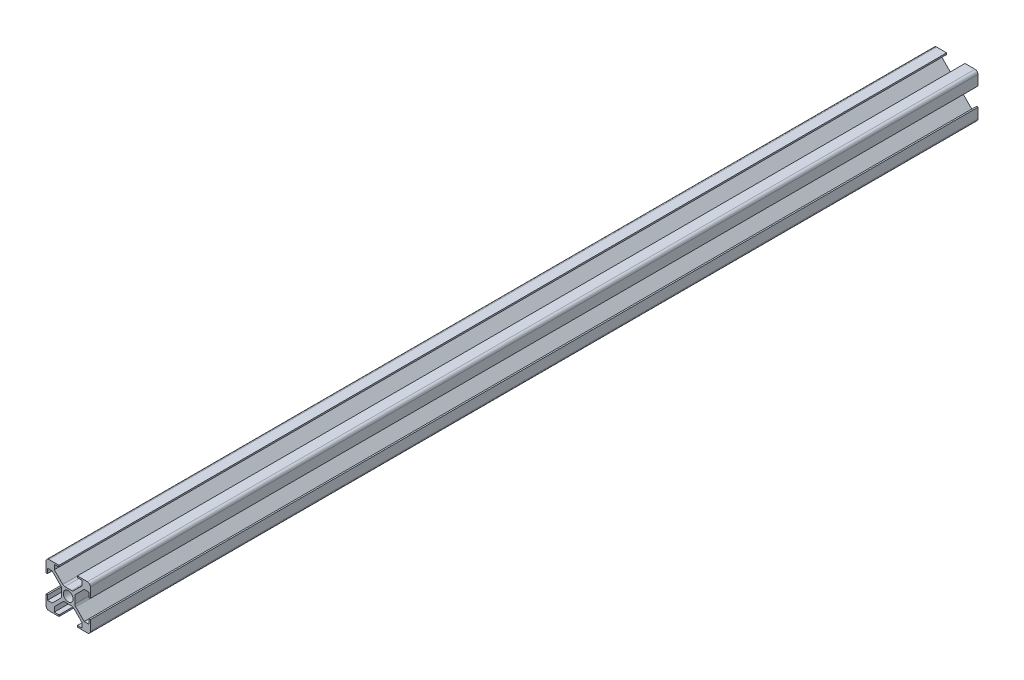
SolidWorks part; units mm, degrees
ref_plane "前视基准面" through (0, 0, 0) normal (0, 0, 1) x (1, 0, 0)
ref_plane "上视基准面" through (0, 0, 0) normal (0, 1, 0) x (1, 0, 0)
ref_plane "右视基准面" through (0, 0, 0) normal (1, 0, 0) x (0, 0, -1)
sketch "草图1" plane through (0, 0, 0) normal (0, 0, 1) x (1, 0, 0)
  line L0 (0, 0) -> (7.5, 0) construction
  line L1 (0, 0) -> (0, 7.5) construction
  line L2 (7.5, 7.5) -> (0, 0) construction
  line L3 (7.5, 7.5) -> (7.5, 3.1)
  line L4 (7.5, 3.1) -> (7, 3.1)
  line L5 (7, 3.1) -> (7, 4.7)
  line L6 (7, 4.7) -> (5.4071, 4.7)
  line L7 (5.4071, 4.7) -> (2.2549, 1.5478)
  line L8 (2.2549, 1.5478) -> (2.2549, 0)
  line L9 (1.5478, 2.2549) -> (0, 2.2549)
  line L10 (4.7, 5.4071) -> (1.5478, 2.2549)
  line L11 (4.7, 7) -> (4.7, 5.4071)
  line L12 (3.1, 7) -> (4.7, 7)
  line L13 (3.1, 7.5) -> (3.1, 7)
  line L14 (7.5, 7.5) -> (3.1, 7.5)
  line L15 (7.5, -7.5) -> (3.1, -7.5)
  line L16 (3.1, -7.5) -> (3.1, -7)
  line L17 (3.1, -7) -> (4.7, -7)
  line L18 (4.7, -7) -> (4.7, -5.4071)
  line L19 (4.7, -5.4071) -> (1.5478, -2.2549)
  line L20 (1.5478, -2.2549) -> (0, -2.2549)
  line L21 (2.2549, -1.5478) -> (2.2549, 0)
  line L22 (5.4071, -4.7) -> (2.2549, -1.5478)
  line L23 (7, -4.7) -> (5.4071, -4.7)
  line L24 (7, -3.1) -> (7, -4.7)
  line L25 (7.5, -3.1) -> (7, -3.1)
  line L26 (7.5, -7.5) -> (7.5, -3.1)
  line L27 (0, 0) -> (7.5, 0) construction
  line L28 (7.5, -7.5) -> (0, 0) construction
  line L29 (-7.5, -7.5) -> (-7.5, -3.1)
  line L30 (-7.5, -3.1) -> (-7, -3.1)
  line L31 (-7, -3.1) -> (-7, -4.7)
  line L32 (-7, -4.7) -> (-5.4071, -4.7)
  line L33 (-5.4071, -4.7) -> (-2.2549, -1.5478)
  line L34 (-2.2549, -1.5478) -> (-2.2549, 0)
  line L35 (-1.5478, -2.2549) -> (0, -2.2549)
  line L36 (-4.7, -5.4071) -> (-1.5478, -2.2549)
  line L37 (-4.7, -7) -> (-4.7, -5.4071)
  line L38 (-3.1, -7) -> (-4.7, -7)
  line L39 (-3.1, -7.5) -> (-3.1, -7)
  line L40 (-7.5, -7.5) -> (-3.1, -7.5)
  line L41 (0, 0) -> (0, -7.5) construction
  line L42 (-7.5, -7.5) -> (0, 0) construction
  line L43 (-7.5, 7.5) -> (-3.1, 7.5)
  line L44 (-3.1, 7.5) -> (-3.1, 7)
  line L45 (-3.1, 7) -> (-4.7, 7)
  line L46 (-4.7, 7) -> (-4.7, 5.4071)
  line L47 (-4.7, 5.4071) -> (-1.5478, 2.2549)
  line L48 (-1.5478, 2.2549) -> (0, 2.2549)
  line L49 (-2.2549, 1.5478) -> (-2.2549, 0)
  line L50 (-5.4071, 4.7) -> (-2.2549, 1.5478)
  line L51 (-7, 4.7) -> (-5.4071, 4.7)
  line L52 (-7, 3.1) -> (-7, 4.7)
  line L53 (-7.5, 3.1) -> (-7, 3.1)
  line L54 (-7.5, 7.5) -> (-7.5, 3.1)
  line L55 (0, 0) -> (-7.5, 0) construction
  line L56 (-7.5, 7.5) -> (0, 0) construction
  circle A0 centre (0, 0) radius 1.65
  point P63 (0, 0)
  dimension "D7" = 3.3
  dimension "D1" = 7.5
  dimension "D2" = 7.5
  dimension "D3" = 4.4
  dimension "D4" = 1.6
  dimension "D5" = 0.5
  dimension "D6" = 0.5
  dimension "D8" = 4
extrude "凸台-拉伸1" add sketch "草图1" along normal blind 300
fillet "圆角1" radius 1 10 edges at (-1.5478, -2.2549, 150) (1.5478, -2.2549, 150) (-2.2549, -1.5478, 150) (-1.5478, 2.2549, 150) (1.5478, 2.2549, 150) (2.2549, -1.5478, 150) (-7.5, -7.5, 150) (7.5, -7.5, 150) (-7.5, 7.5, 150) (7.5, 7.5, 150)
